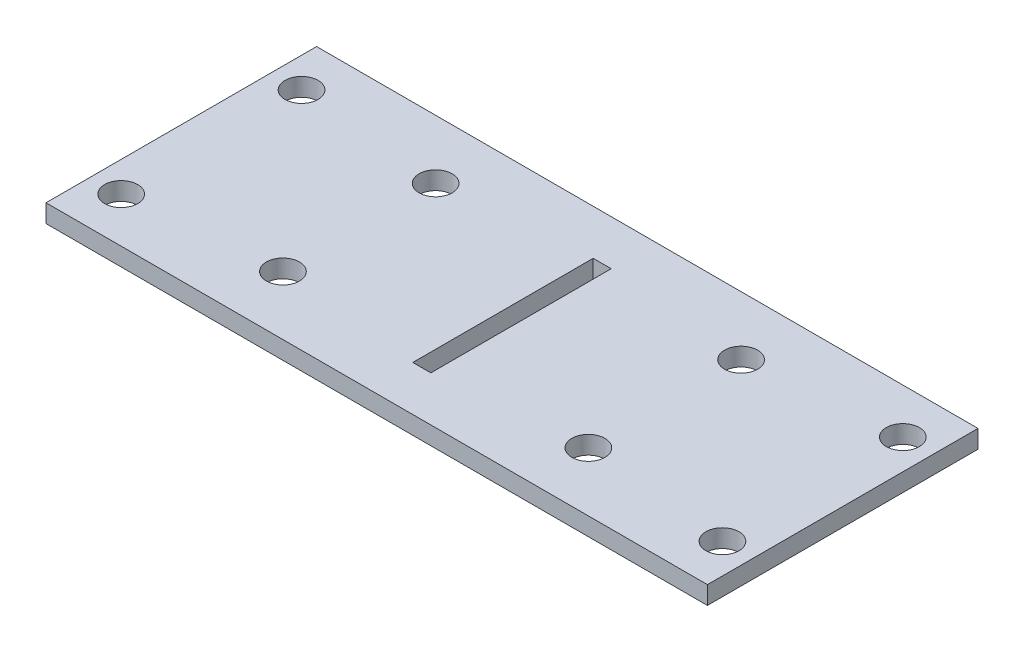
SolidWorks part; units mm, degrees
material "Acrylic (Medium-high impact)"
ref_plane "Front Plane" through (0, 0, 0) normal (0, 0, 1) x (1, 0, 0)
ref_plane "Top Plane" through (0, 0, 0) normal (0, 1, 0) x (1, 0, 0)
ref_plane "Right Plane" through (0, 0, 0) normal (1, 0, 0) x (0, 0, -1)
sketch "Sketch1" plane through (0, 0, 0) normal (0, 1, 0) x (1, 0, 0)
  line L1 (-55, -22.5) -> (55, -22.5)
  line L2 (-55, -22.5) -> (-55, 22.5)
  line L3 (-55, 22.5) -> (55, 22.5)
  line L4 (55, -22.5) -> (55, 22.5)
  line L5 (-55, -22.5) -> (55, 22.5) construction
  line L6 (-55, 22.5) -> (55, -22.5) construction
  line L7 (-50, 15) -> (50, 15) construction
  line L8 (-50, 15) -> (-50, -15) construction
  line L9 (-50, -15) -> (50, -15) construction
  line L10 (50, 15) -> (50, -15) construction
  line L11 (-50, 15) -> (50, -15) construction
  line L12 (-50, -15) -> (50, 15) construction
  line L13 (-1.5, -15) -> (1.5, -15)
  line L14 (-1.5, -15) -> (-1.5, 15)
  line L15 (-1.5, 15) -> (1.5, 15)
  line L16 (1.5, -15) -> (1.5, 15)
  line L17 (-1.5, -15) -> (1.5, 15) construction
  line L18 (-1.5, 15) -> (1.5, -15) construction
  point P0 (0, 0)
  point P6 (0, 0)
  point P11 (0, 0)
  dimension "D1" = 45
  dimension "D2" = 110
  dimension "D3" = 100
  dimension "D4" = 30
  dimension "D5" = 3
extrude "Boss-Extrude1" add sketch "Sketch1" along normal blind 3
hole_wizard "M5 Clearance Hole2" positions "Sketch2" profile "Sketch3" hole size "M5" standard "ANSI Metric"
sketch "Sketch2" plane through (0, 3, 0) normal (0, 1, 0) x (1, 0, 0)
  line L1 (-50, -15) -> (50, -15)
  line L2 (-50, -15) -> (-50, 15)
  line L3 (-50, 15) -> (50, 15)
  line L4 (50, -15) -> (50, 15)
  line L5 (-50, -15) -> (50, 15) construction
  line L6 (-50, 15) -> (50, -15) construction
  point P2 (50, 15)
  point P95 (-50, -15)
  point P96 (-50, 15)
  point P97 (50, -15)
  point P110 (0, 0)
  point P111 (0, 0)
  dimension "D1" = 30
  dimension "D2" = 100
sketch "Sketch3" plane through (50, 3, -15) normal (1, 0, 0) x (0, 0, 1)
  line L0 (0, 0) -> (0, 14.0524)
  line L1 (0, 14.0524) -> (2.75, 12.4)
  line L2 (2.75, 12.4) -> (2.75, 0)
  line L5 (2.75, 0) -> (0, 0)
  line L10 (0, 14.0524) -> (-2.75, 12.4) construction
  line L11 (0, -6.35) -> (0, 107.95) construction
  dimension "Hole Dia." = 5.5
  dimension "Hole Depth" = 12.4
  dimension "Drill Angle" = 118
hole_wizard "M5 Clearance Hole3" positions "Sketch7" profile "Sketch8" hole size "M5" standard "ANSI Metric" end condition through all
sketch "Sketch7" plane through (0, 3, 0) normal (0, 1, 0) x (1, 0, 0)
  line L1 (-25.4, -12.7) -> (25.4, -12.7)
  line L2 (-25.4, -12.7) -> (-25.4, 12.7)
  line L3 (-25.4, 12.7) -> (25.4, 12.7)
  line L4 (25.4, -12.7) -> (25.4, 12.7)
  point P1 (-25.4, -12.7)
  point P2 (25.4, 12.7)
  point P39 (-25.4, 12.7)
  point P40 (25.4, -12.7)
  point P42 (25.4, 0)
  point P44 (0, -12.7)
  dimension "D1" = 25.4
  dimension "D2" = 50.8
sketch "Sketch8" plane through (-25.4, 3, 12.7) normal (1, 0, 0) x (0, 0, 1)
  line L0 (0, 0) -> (0, 3)
  line L1 (0, 3) -> (2.75, 3)
  line L2 (2.75, 3) -> (2.75, 0)
  line L5 (2.75, 0) -> (0, 0)
  line L11 (0, -6.35) -> (0, 107.95) construction
  dimension "Thru Hole Dia." = 5.5
  dimension "Thru Hole Depth" = 3
